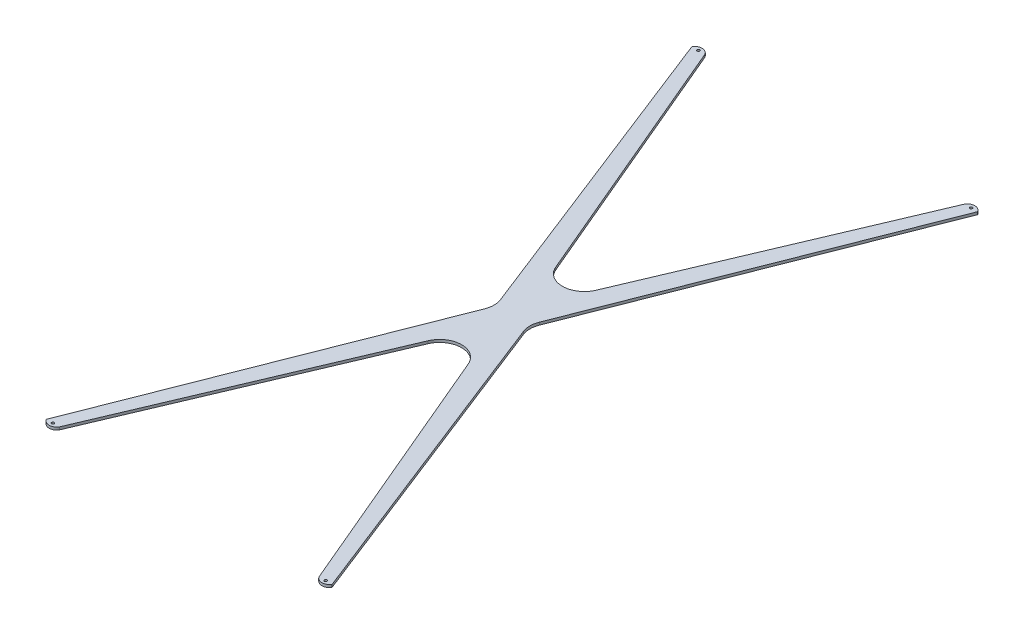
SolidWorks part; units mm, degrees
ref_plane "Front Plane" through (0, 0, 0) normal (0, 0, 1) x (1, 0, 0)
ref_plane "Top Plane" through (0, 0, 0) normal (0, 1, 0) x (1, 0, 0)
ref_plane "Right Plane" through (0, 0, 0) normal (1, 0, 0) x (0, 0, -1)
sketch "Sketch1" plane through (0, 0, 0) normal (0, 1, 0) x (1, 0, 0)
  line L0 (0, 0) -> (1250, 2959) construction
  line L1 (0, 0) -> (1250, 0) construction
  line L2 (0, 0) -> (0, 2959) construction
  line L3 (0, 2959) -> (1250, 2959) construction
  line L4 (1250, 0) -> (1250, 2959) construction
  line L5 (0, 2959) -> (1250, 0) construction
  line L6 (-30, 2959) -> (30, 2959) construction
  line L7 (1220, 2959) -> (1280, 2959) construction
  line L8 (1220, 0) -> (1280, 0) construction
  line L9 (-30, 0) -> (30, 0) construction
  line L10 (625, 1404.5) -> (625, 1554.5) construction
  line L11 (550, 1479.5) -> (700, 1479.5) construction
  line L12 (550, 1479.5) -> (-30, 2959)
  line L13 (30, 2959) -> (625, 1554.5)
  line L14 (625, 1554.5) -> (1220, 2959)
  line L15 (550, 1479.5) -> (-30, 0)
  line L16 (30, 0) -> (625, 1404.5)
  line L17 (625, 1404.5) -> (1220, 0)
  line L18 (1280, 0) -> (700, 1479.5)
  line L19 (700, 1479.5) -> (1280, 2959)
  line L20 (0, 2959) -> (0, 2976) construction
  circle A0 centre (0, 2959) radius 6
  circle A1 centre (1250, 2959) radius 6
  circle A2 centre (1250, 0) radius 6
  circle A3 centre (0, 0) radius 6
  arc A4 (-30, 2959) -> (30, 2959) centre (0, 2941.0294) cw
  arc A5 (1280, 2959) -> (1220, 2959) centre (1250, 2941.0294) ccw
  arc A6 (-30, 0) -> (30, 0) centre (0, 17.9706) ccw
  arc A7 (1280, 0) -> (1220, 0) centre (1250, 17.9706) cw
  point P15 (625, 1479.5)
  dimension "D6" = 12
  dimension "D1" = 2959
  dimension "D2" = 1250
  dimension "D3" = 60
  dimension "D4" = 150
  dimension "D5" = 150
  dimension "D7" = 17
extrude "Boss-Extrude1" add sketch "Sketch1" along normal blind 12
fillet "Fillet1" radius 100 4 edges at (550, 6, -1479.5) (625, 6, -1554.5) (700, 6, -1479.5) (625, 6, -1404.5)
equation "\"mbtOD\" = 500"
equation "\"mbtT\" = 6"
equation "\"mbtL\" = 3000"
equation "\"mbtFlangeOD\" = 650"
equation "\"mbtFlangeT\" = 12"
equation "\"mbtFlangeBoltCircleDia\" = 650"
equation "\"mbtFlangeHoleDia\" = 12"
equation "\"mbtOringSize\" = 10 "
equation "\"mbtOringDia\" = 620"
equation "\"mbtWidth\" = 2250"
equation "\"skiWidth\" = 1250"
equation "\"D1@Sketch1\"=\"mbtL\"+2*\"mbtFlangeT\"-65mm"
equation "\"D2@Sketch1\"=\"skiWidth\""
equation "\"D1@Boss-Extrude1\"=\"mbtFlangeT\""
